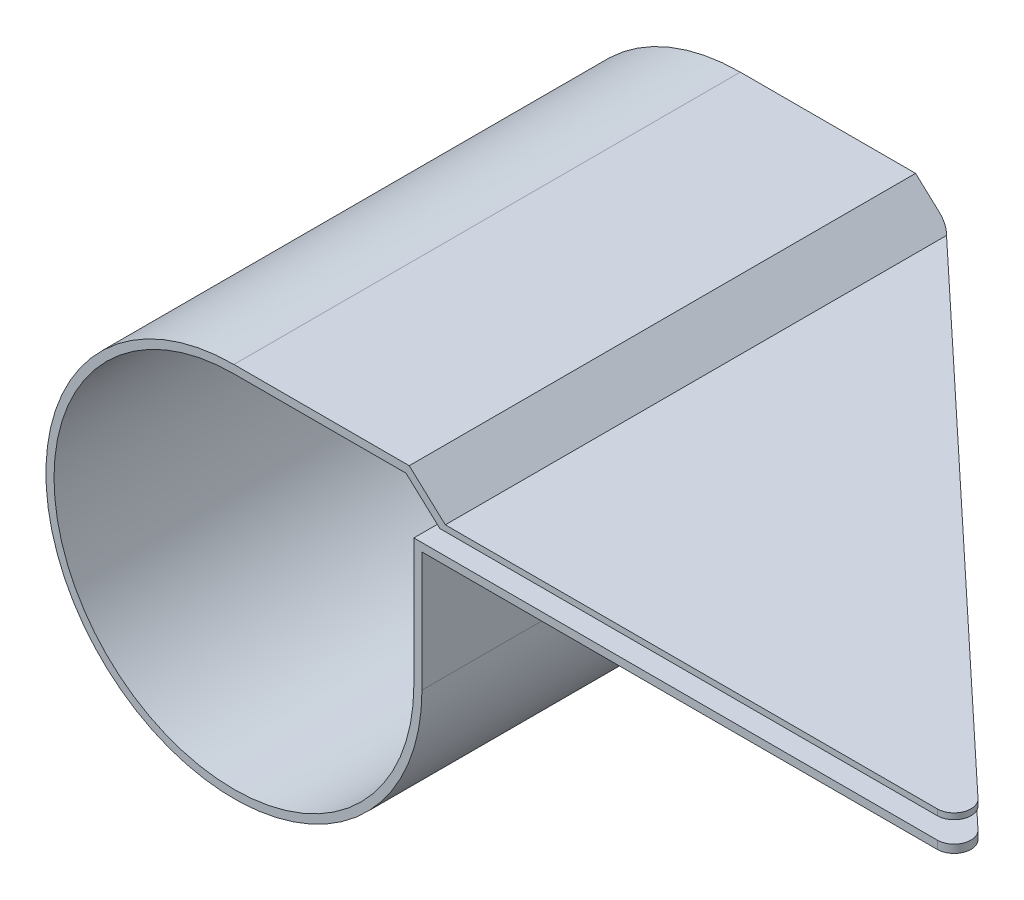
SolidWorks part; units mm, degrees
ref_plane "Front Plane" through (0, 0, 0) normal (0, 0, 1) x (1, 0, 0)
ref_plane "Top Plane" through (0, 0, 0) normal (0, 1, 0) x (1, 0, 0)
ref_plane "Right Plane" through (0, 0, 0) normal (1, 0, 0) x (0, 0, -1)
sketch "Sketch1" plane through (0, 0, 0) normal (0, 0, 1) x (1, 0, 0)
  line L0 (0, 30.988) -> (0, -30.988) construction
  line L1 (-30.988, -30.988) -> (30.988, -30.988)
  line L2 (-30.988, -30.988) -> (-30.988, 30.988)
  line L3 (-30.988, 30.988) -> (30.988, 30.988)
  line L4 (30.988, -30.988) -> (30.988, 30.988)
  line L5 (-30.988, -30.988) -> (30.988, 30.988) construction
  line L6 (-30.988, 30.988) -> (30.988, -30.988) construction
  line L7 (-30.988, 0) -> (30.988, 0) construction
  circle A0 centre (0, 0) radius 27.0764
  circle A1 centre (-23.368, 23.368) radius 2.54
  circle A2 centre (-23.368, -23.368) radius 2.54
  circle A3 centre (23.368, -23.368) radius 2.54
  circle A4 centre (23.368, 23.368) radius 2.54
  point P20 (0, 0)
  dimension "D1" = 54.1528
  dimension "D2" = 5.08
  dimension "D3" = 7.62
  dimension "D4" = 61.976
sketch "Sketch2" plane through (0, 0, 0) normal (0, 0, 1) x (1, 0, 0)
  line L0 (30.988, 30.988) -> (30.988, 22.4053)
  line L1 (30.988, -30.988) -> (30.988, 30.988) construction
  line L2 (30.988, 22.4053) -> (30.988, 19.2303)
  line L3 (0, 27.0764) -> (25.908, 27.0764)
  line L4 (25.908, 23.368) -> (25.908, 27.0764) construction
  line L5 (25.908, 27.0764) -> (30.988, 22.4053)
  line L6 (30.988, 22.4053) -> (112.268, 22.4053)
  line L7 (27.0764, 0) -> (27.0764, 19.2303)
  line L8 (27.0764, 19.2303) -> (112.268, 19.2303)
  line L9 (28.2956, 18.0111) -> (112.268, 18.0111)
  line L10 (28.2956, 0) -> (28.2956, 18.0111)
  line L11 (0, 28.2956) -> (26.3833, 28.2956)
  line L12 (26.3833, 28.2956) -> (31.8132, 23.3028)
  line L13 (31.8132, 23.3028) -> (112.268, 23.3028)
  line L14 (112.268, 23.3028) -> (112.268, 22.4053)
  line L15 (112.268, 19.2303) -> (112.268, 18.0111)
  arc A0 (0, 27.0764) -> (27.0764, 0) centre (0, 0) ccw
  circle A1 centre (23.368, 23.368) radius 2.54 construction
  circle A2 centre (0, 0) radius 27.0764 construction
  arc A3 (0, 28.2956) -> (28.2956, 0) centre (0, 0) ccw
  point P27 (0, 0)
  dimension "D1" = 8.5827
  dimension "D2" = 3.175
  dimension "D3" = 81.28
  dimension "D4" = 1.2192
extrude "Boss-Extrude1" add sketch "Sketch2" along normal blind 76.2 contours L14 L13 L12 L0 L6 | L11 A3 L10 L9 L15 L8 L7 A0 L3 L5 L0 L12
sketch "Sketch3" plane through (0, 18.0111, 0) normal (0, -1, 0) x (1, 0, 0)
  line L0 (27.0764, 76.2) -> (27.0764, 0) construction
  line L1 (27.0764, 76.2) -> (27.0764, 0)
  line L2 (27.0764, 76.2) -> (31.1658, 76.2)
  line L3 (28.2956, 76.2) -> (112.268, 76.2) construction
  line L4 (31.1658, 76.2) -> (30.988, 0)
  line L5 (31.1658, 76.2) -> (112.268, 76.2)
  line L6 (112.268, 76.2) -> (30.988, 0)
  line L7 (30.988, 0) -> (112.268, 0)
  line L8 (112.268, 0) -> (112.268, 76.2)
  line M5 (28.2956, 0) -> (112.268, 0)
  line M6 (112.268, 0) -> (112.268, 76.2)
  dimension "D1" = 4.0894
extrude "Cut-Extrude1" cut sketch "Sketch3" against normal through all contours L6 M6 M5
fillet "Fillet1" radius 2.54 4 edges at (112.268, 22.8541, 76.2) (112.268, 18.6207, 76.2) (30.988, 23.2335, 0) (30.988, 18.6207, 0)
